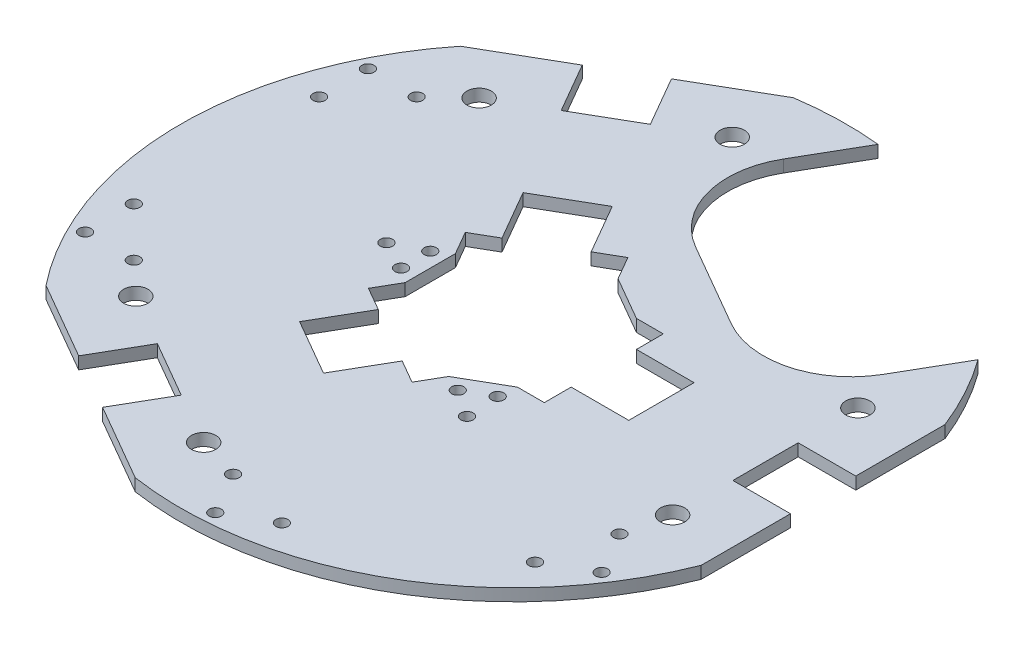
SolidWorks part; units mm, degrees
ref_plane "Front Plane" through (0, 0, 0) normal (0, 0, 1) x (1, 0, 0)
ref_plane "Top Plane" through (0, 0, 0) normal (0, 1, 0) x (1, 0, 0)
ref_plane "Right Plane" through (0, 0, 0) normal (1, 0, 0) x (0, 0, -1)
sketch "Sketch1" plane through (0, 0, 0) normal (0, 1, 0) x (1, 0, 0)
  line L0 (0, 0) -> (101.6, 0)
  line L1 (0, 0) -> (-50.8, 87.9882)
  line L2 (0, 0) -> (-50.8, -87.9882)
  line L3 (20, -12.3081) -> (83, -12.3081)
  line L4 (20, -12.3081) -> (20, 12.3081)
  line L5 (83, -12.3081) -> (83, 12.3081)
  line L6 (20, 12.3081) -> (83, 12.3081)
  line L7 (20, -12.3081) -> (83, 12.3081) construction
  line L8 (83, -12.3081) -> (20, 12.3081) construction
  line L9 (83, 0) -> (83, -58.5966) construction
  line L10 (20, 12.3081) -> (0, 12.3081)
  line L11 (20, 12.3081) -> (20, -12.3081)
  line L12 (20, -12.3081) -> (0, -12.3081)
  line L13 (0, 12.3081) -> (0, -12.3081)
  line L14 (51.5, 12.3081) -> (51.5, -12.3081) construction
  line L15 (83, -58.5966) -> (119.7868, -58.5966)
  line L16 (83, -58.5966) -> (83, 61.6733)
  line L17 (83, 61.6733) -> (119.7868, 61.6733)
  line L18 (119.7868, -58.5966) -> (119.7868, 61.6733)
  line L19 (83, -8.5) -> (20, -8.5)
  line L20 (83, -8.5) -> (83, 8.5)
  line L21 (83, 8.5) -> (20, 8.5)
  line L22 (20, -8.5) -> (20, 8.5)
  line L23 (83, -8.5) -> (20, 8.5) construction
  line L24 (83, 8.5) -> (20, -8.5) construction
  line L25 (20, 8.5) -> (40, 8.5)
  line L26 (20, 8.5) -> (20, 12.3081)
  line L27 (20, 12.3081) -> (40, 12.3081)
  line L28 (40, 8.5) -> (40, 12.3081)
  line L29 (63, 8.5) -> (63, 12.3081)
  line L30 (63, -8.5) -> (63, -12.3081)
  line L31 (40, -8.5) -> (40, -12.3081)
  circle A0 centre (0, 0) radius 101.6
  circle A1 centre (0, 0) radius 20
  point P7 (51.5, 0)
  point P19 (51.5, 0)
  dimension "D1" = 120
  dimension "D8" = 203.2
  dimension "D2" = 120
  dimension "D3" = 63
  dimension "D4" = 20
  dimension "D5" = 0
  dimension "D6" = 17
  dimension "D7" = 20
sketch "Sketch2" plane through (0, 0, 0) normal (0, 1, 0) x (1, 0, 0)
  circle A0 centre (0, 0) radius 88.9
  dimension "D1" = 177.8
extrude "Boss-Extrude1" add sketch "Sketch2" along normal blind 3.175
sketch "Sketch4" plane through (0, 3.175, 0) normal (0, 1, 0) x (1, 0, 0)
  line L0 (-88.9, 0) -> (88.9, 0) construction
  line L1 (52.07, 0) -> (52.07, 13.9847) construction
  line L2 (16.51, 15.5) -> (38.51, 15.5)
  line L3 (16.51, 15.5) -> (16.51, -15.5)
  line L4 (16.51, -15.5) -> (38.51, -15.5)
  line L5 (38.51, 15.5) -> (38.51, -15.5)
  line L6 (16.51, 15.5) -> (38.51, -15.5) construction
  line L7 (16.51, -15.5) -> (38.51, 15.5) construction
  line L8 (-16.51, -16.51) -> (16.51, -16.51)
  line L9 (-16.51, -16.51) -> (-16.51, 16.51)
  line L10 (-16.51, 16.51) -> (16.51, 16.51)
  line L11 (16.51, -16.51) -> (16.51, 16.51)
  line L12 (-16.51, -16.51) -> (16.51, 16.51) construction
  line L13 (-16.51, 16.51) -> (16.51, -16.51) construction
  line L14 (16.51, 15.5) -> (23.51, 15.5)
  line L15 (16.51, 15.5) -> (16.51, -15.5)
  line L16 (16.51, -15.5) -> (23.51, -15.5)
  line L17 (23.51, 15.5) -> (23.51, -15.5)
  line L18 (23.51, 8.5) -> (38.51, 8.5)
  line L19 (23.51, 8.5) -> (23.51, -8.5)
  line L20 (23.51, -8.5) -> (38.51, -8.5)
  line L21 (38.51, 8.5) -> (38.51, -8.5)
  line L22 (80.63, -8.5) -> (65.63, -8.5)
  line L23 (65.63, 8.5) -> (65.63, -8.5)
  line L24 (80.63, 8.5) -> (65.63, 8.5)
  line L25 (80.63, 8.5) -> (80.63, -8.5)
  line L26 (87.63, -15.5) -> (65.63, -15.5)
  line L27 (65.63, 15.5) -> (65.63, -15.5)
  line L28 (87.63, 15.5) -> (65.63, 15.5)
  line L29 (87.63, 15.5) -> (87.63, -15.5)
  line L30 (87.63, -15.5) -> (80.63, -15.5)
  line L31 (80.63, 15.5) -> (80.63, -15.5)
  line L32 (87.63, 15.5) -> (80.63, 15.5)
  line L33 (87.63, 15.5) -> (87.63, -15.5)
  line L34 (80.63, -31.75) -> (80.63, 31.75)
  line L35 (80.63, -31.75) -> (102.0422, -31.75)
  line L36 (80.63, 31.75) -> (102.0422, 31.75)
  line L37 (102.0422, -31.75) -> (102.0422, 31.75)
  circle A1 centre (0, 0) radius 88.9
  circle A2 centre (0, 0) radius 88.9
  point P5 (27.51, 0)
  dimension "D2" = 22
  dimension "D3" = 33.02
  dimension "D4" = 33.02
  dimension "D5" = 31
  dimension "D6" = 0
  dimension "D7" = 7
  dimension "D8" = 17
  dimension "D9" = 8.5
  dimension "D10" = 35.56
  dimension "D11" = 63.5
  dimension "D12" = 31.75
  dimension "D1" = 0
extrude "Cut-Extrude2" cut sketch "Sketch4" against normal through all contours L17 L2 L3 L4 | L25 L24 L23 L22 | L17 L20 L5 L18 | L34 L35 L37 L36
pattern_circular "CirPattern1" count 3 over 360 about axis through (0, 0, 0) along (0, 1, 0) of "Cut-Extrude2"
sketch "Sketch5" plane through (0, 3.175, 0) normal (0, 1, 0) x (1, 0, 0)
  line L1 (-16.51, -15.5) -> (16.51, -15.5)
  line L2 (-16.51, -15.5) -> (-16.51, 15.5)
  line L3 (-16.51, 15.5) -> (16.51, 15.5)
  line L4 (16.51, -15.5) -> (16.51, 15.5)
  line L5 (-16.51, -15.5) -> (16.51, 15.5) construction
  line L6 (-16.51, 15.5) -> (16.51, -15.5) construction
  line L7 (-5.49, -15.5) -> (16.51, -15.5)
  line L8 (-5.49, -15.5) -> (-5.49, 15.5)
  line L9 (-5.49, 15.5) -> (16.51, 15.5)
  line L10 (16.51, -15.5) -> (16.51, 15.5)
  line L11 (-5.49, -15.5) -> (16.51, 15.5) construction
  line L12 (-5.49, 15.5) -> (16.51, -15.5) construction
  point P0 (0, 0)
  point P7 (5.51, 0)
  dimension "D1" = 22
sketch "Sketch6" plane through (0, 3.175, 0) normal (0, 1, 0) x (1, 0, 0)
  line L0 (5.1684, 22.0481) -> (16.51, 15.5)
  line L1 (16.51, 15.5) -> (16.51, -15.5)
  line L2 (16.51, -15.5) -> (5.1684, -22.0481)
  line L3 (5.1684, -22.0481) -> (-21.6784, -6.5481)
  line L4 (-21.6784, -6.5481) -> (-21.6784, 6.5481)
  line L5 (-21.6784, 6.5481) -> (5.1684, 22.0481)
  line L21 (-32.9538, -74.0776) -> (-12.8187, -85.7026)
  line L24 (80.63, -31.75) -> (80.63, -8.5)
  line L25 (80.63, -8.5) -> (65.63, -8.5)
  line L26 (65.63, -8.5) -> (65.63, 8.5)
  line L27 (65.63, 8.5) -> (80.63, 8.5)
  line L28 (80.63, 8.5) -> (80.63, 31.75)
  line L31 (-12.8187, 85.7026) -> (-32.9538, 74.0776)
  line L32 (-32.9538, 74.0776) -> (-25.4538, 61.0872)
  line L33 (-25.4538, 61.0872) -> (-40.1762, 52.5872)
  line L34 (-40.1762, 52.5872) -> (-47.6762, 65.5776)
  line L35 (-47.6762, 65.5776) -> (-67.8113, 53.9526)
  line L38 (-67.8113, -53.9526) -> (-47.6762, -65.5776)
  line L39 (-47.6762, -65.5776) -> (-40.1762, -52.5872)
  line L40 (-40.1762, -52.5872) -> (-25.4538, -61.0872)
  line L41 (-25.4538, -61.0872) -> (-32.9538, -74.0776)
  line L42 (-32.9538, -74.0776) -> (-12.8187, -85.7026)
  line L45 (80.63, -31.75) -> (80.63, -8.5)
  line L46 (80.63, -8.5) -> (65.63, -8.5)
  line L47 (65.63, -8.5) -> (65.63, 8.5)
  line L48 (65.63, 8.5) -> (80.63, 8.5)
  line L49 (80.63, 8.5) -> (80.63, 31.75)
  line L52 (-12.8187, 85.7026) -> (-32.9538, 74.0776)
  line L53 (-32.9538, 74.0776) -> (-25.4538, 61.0872)
  line L54 (-25.4538, 61.0872) -> (-40.1762, 52.5872)
  line L55 (-40.1762, 52.5872) -> (-47.6762, 65.5776)
  line L56 (-47.6762, 65.5776) -> (-67.8113, 53.9526)
  line L59 (-67.8113, -53.9526) -> (-47.6762, -65.5776)
  line L60 (-47.6762, -65.5776) -> (-40.1762, -52.5872)
  line L61 (-40.1762, -52.5872) -> (-25.4538, -61.0872)
  line L62 (-25.4538, -61.0872) -> (-32.9538, -74.0776)
  line L63 (-12.8187, -85.7026) -> (-14.0222, -87.7872)
  line L64 (-12.8187, -85.7026) -> (-14.0222, -87.7872)
  line L65 (83.037, -31.75) -> (80.63, -31.75)
  line L66 (83.037, -31.75) -> (80.63, -31.75)
  line L67 (80.63, 31.75) -> (83.037, 31.75)
  line L68 (80.63, 31.75) -> (83.037, 31.75)
  line L69 (-14.0222, 87.7872) -> (-12.8187, 85.7026)
  line L70 (-14.0222, 87.7872) -> (-12.8187, 85.7026)
  line L71 (-67.8113, 53.9526) -> (-69.0148, 56.0372)
  line L72 (-67.8113, 53.9526) -> (-69.0148, 56.0372)
  line L73 (-69.0148, -56.0372) -> (-67.8113, -53.9526)
  line L74 (-69.0148, -56.0372) -> (-67.8113, -53.9526)
  arc A3 (-14.0222, -87.7872) -> (83.037, -31.75) centre (0, 0) ccw
  arc A5 (-14.0222, -87.7872) -> (83.037, -31.75) centre (0, 0) ccw
  arc A10 (83.037, 31.75) -> (-14.0222, 87.7872) centre (0, 0) ccw
  arc A12 (83.037, 31.75) -> (-14.0222, 87.7872) centre (0, 0) ccw
  arc A13 (-69.0148, 56.0372) -> (-69.0148, -56.0372) centre (0, 0) ccw
  arc A14 (-69.0148, 56.0372) -> (-69.0148, -56.0372) centre (0, 0) ccw
  line M38 (16.51, -15.5) -> (16.51, 15.5)
  line M46 (-21.6784, -6.5481) -> (5.1684, -22.0481)
  line M78 (5.1684, 22.0481) -> (-21.6784, 6.5481)
  dimension "D1" = 0
extrude "Cut-Extrude3" cut sketch "Sketch6" against normal through all contours L4 L2 L0 M46 M38 M78
sketch "Sketch8" plane through (0, 3.175, 0) normal (0, 1, 0) x (1, 0, 0)
  circle A0 centre (0, 0) radius 86.656
extrude "Cut-Extrude-Thin1" cut sketch "Sketch8" against normal through all thin
sketch "Sketch9" plane through (0, 3.175, 0) normal (0, 1, 0) x (1, 0, 0)
  line L0 (0, 0) -> (98.7445, 0) construction
  line L2 (8.8329, -24.13) -> (65.5497, -24.13)
  line L3 (8.8329, -24.13) -> (8.8329, 24.13)
  line L4 (8.8329, 24.13) -> (65.5497, 24.13)
  line L5 (65.5497, -24.13) -> (65.5497, 24.13)
  line L6 (8.8329, -24.13) -> (65.5497, 24.13) construction
  line L7 (8.8329, 24.13) -> (65.5497, -24.13) construction
  circle A0 centre (0, 0) radius 69.85
  circle A1 centre (65.5497, 24.13) radius 3.175
  circle A2 centre (65.5497, -24.13) radius 3.175
  point P3 (37.1913, 0)
  dimension "D1" = 48.26
  dimension "D2" = 139.7
extrude "Cut-Extrude4" cut sketch "Sketch9" against normal through all contours A1 | A2
pattern_circular "CirPattern2" count 3 over 360 about axis through (0, 0, 0) along (0, 1, 0) of "Cut-Extrude4"
sketch "Sketch10" plane through (0, 3.175, 0) normal (0, 1, 0) x (1, 0, 0)
  line L0 (43.328, 75.0463) -> (0, 0)
  line L1 (49.8459, 15.2156) -> (75.2459, 59.2097)
  line L2 (49.8459, 15.2156) -> (-11.7459, 50.7756)
  line L3 (75.2459, 59.2097) -> (13.6541, 94.7697)
  line L4 (-11.7459, 50.7756) -> (13.6541, 94.7697)
  line L5 (49.8459, 15.2156) -> (13.6541, 94.7697) construction
  line L6 (75.2459, 59.2097) -> (-11.7459, 50.7756) construction
  circle A0 centre (43.328, 75.0463) radius 38.1
  arc A1 (80.63, 31.75) -> (-12.8187, 85.7026) centre (0, 0) ccw construction
  point P8 (31.75, 54.9926)
  dimension "D1" = 71.12
  dimension "D2" = 35.56
  dimension "D3" = 50.8
  dimension "D4" = 63.5
sketch "Sketch11" plane through (0, 3.175, 0) normal (0, 1, 0) x (1, 0, 0)
  line L0 (-21.6784, -6.5481) -> (-21.6784, 6.5481) construction
  line L1 (0, 0) -> (-111.2988, 0)
  line L2 (-23.9644, -36.83) -> (-74.7644, -36.83)
  line L3 (-23.9644, -36.83) -> (-23.9644, 36.83)
  line L4 (-23.9644, 36.83) -> (-74.7644, 36.83)
  line L5 (-74.7644, -36.83) -> (-74.7644, 36.83)
  line L6 (-23.9644, -36.83) -> (-74.7644, 36.83) construction
  line L7 (-23.9644, 36.83) -> (-74.7644, -36.83) construction
  line L12 (-23.9644, -6.35) -> (-23.9644, 6.35)
  line L16 (-23.9644, 6.35) -> (-23.9644, -6.35)
  line L19 (-76.3519, 36.83) -> (-73.1769, 36.83)
  line L20 (-76.3519, 36.83) -> (-76.3519, 24.13)
  line L21 (-76.3519, 24.13) -> (-73.1769, 24.13)
  line L22 (-73.1769, 36.83) -> (-73.1769, 24.13)
  line L23 (-74.7644, 38.4175) -> (-62.0644, 38.4175)
  line L24 (-74.7644, 38.4175) -> (-74.7644, 35.2425)
  line L25 (-74.7644, 35.2425) -> (-62.0644, 35.2425)
  line L26 (-62.0644, 38.4175) -> (-62.0644, 35.2425)
  line L28 (-23.9644, 0) -> (-23.9644, 3.81)
  circle A0 centre (-74.7644, 36.83) radius 1.5875
  circle A1 centre (-62.0644, 36.83) radius 1.5875
  circle A2 centre (-74.7644, 24.13) radius 1.5875
  circle A4 centre (-74.7644, 36.83) radius 3.175
  point P3 (-49.3644, 0)
  point P8 (-23.2024, 0)
  dimension "D7" = 3.175
  dimension "D8" = 3.175
  dimension "D9" = 3.175
  dimension "D6" = 6.35
  dimension "D1" = 50.8
  dimension "D2" = 73.66
  dimension "D3" = 2.286
  dimension "D4" = 0
  dimension "D5" = 0
  dimension "D10" = 12.7
  dimension "D11" = 12.7
extrude "Cut-Extrude6" cut sketch "Sketch11" against normal through all
mirror "Mirror1" about plane through (0, 0, 0) normal (0, 0, 1) of "Cut-Extrude6"
pattern_circular "CirPattern3" count 2 every 120 about axis through (0, 0, 0) along (0, 1, 0) of "Mirror1", "Cut-Extrude6"
sketch "Sketch12" plane through (0, 3.175, 0) normal (0, 1, 0) x (1, 0, 0)
  line L2 (0, 0) -> (-49.928, 0) construction
  line L3 (-21.6784, -6.5481) -> (-21.6784, 6.5481) construction
  line L4 (-25.4884, -6.35) -> (-21.6784, -6.35)
  line L5 (-25.4884, -6.35) -> (-25.4884, 6.35)
  line L6 (-25.4884, 6.35) -> (-21.6784, 6.35)
  line L7 (-21.6784, -6.35) -> (-21.6784, 6.35)
  line L8 (-25.4884, -6.35) -> (-21.6784, 6.35) construction
  line L9 (-25.4884, 6.35) -> (-21.6784, -6.35) construction
  line L12 (-25.4884, 6.35) -> (-25.4884, -6.35)
  circle A0 centre (-25.4884, 3.81) radius 1.5875
  circle A1 centre (-25.4884, -3.81) radius 1.5875
  circle A2 centre (-33.1084, 0) radius 1.5875
  point P0 (-23.5834, 0)
  dimension "D3" = 3.175
  dimension "D4" = 3.175
  dimension "D7" = 3.175
  dimension "D1" = 3.81
  dimension "D2" = 12.7
  dimension "D5" = 7.62
  dimension "D6" = 3.81
  dimension "D8" = 7.62
extrude "Cut-Extrude7" cut sketch "Sketch12" against normal through all contours A2 | L12 A0 | L12 A0 | L12 A1 | L12 A1
pattern_circular "CirPattern4" count 2 every 120 about axis through (0, 0, 0) along (0, 1, 0) of "Cut-Extrude7"
extrude "Cut-Extrude8" cut sketch "Sketch10" against normal blind 150 contours L3 L4 L2 L1
fillet "Fillet1" radius 22.86 2 edges at (49.8459, 1.5875, -15.2156) (-11.7459, 1.5875, -50.7756)
